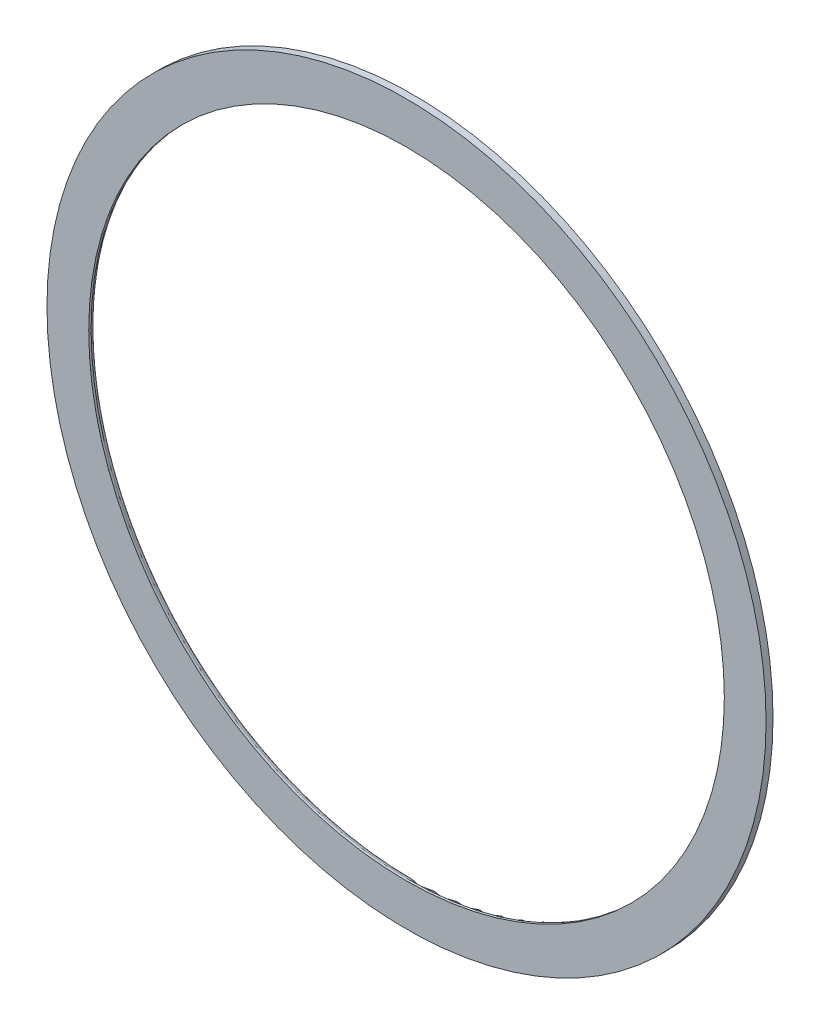
SolidWorks part; units mm, degrees
ref_plane "前视基准面" through (0, 0, 0) normal (0, 0, 1) x (1, 0, 0)
ref_plane "上视基准面" through (0, 0, 0) normal (0, 1, 0) x (1, 0, 0)
ref_plane "右视基准面" through (0, 0, 0) normal (1, 0, 0) x (0, 0, -1)
other "Configuration Table"
sketch "草图1" plane through (0, 0, 0) normal (0, 0, 1) x (1, 0, 0)
  circle A0 centre (0, 0) radius 77.5
extrude "拉伸-薄壁1" add sketch "草图1" along normal blind 1.5 thin thin type one direction reverse wall 9
fillet "圆角1" radius 1 1 edges at (68.5, 0, 0)
